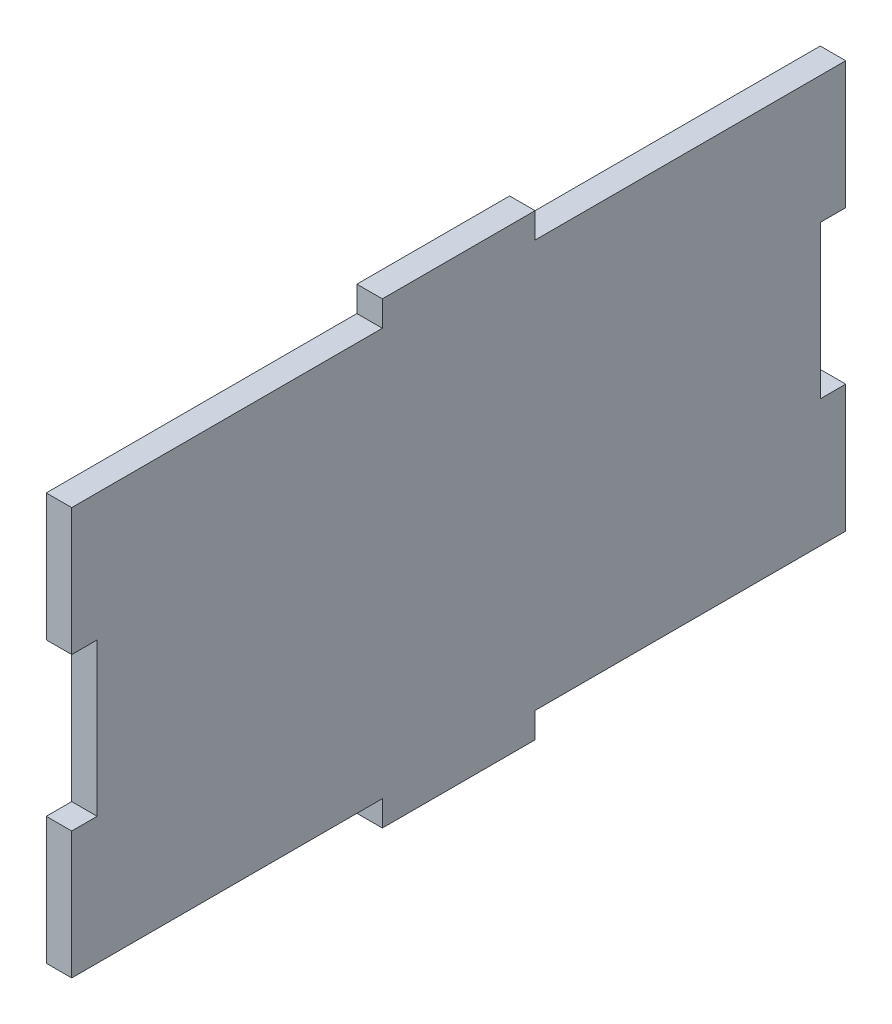
SolidWorks part; units mm, degrees
ref_plane "Front Plane" through (0, 0, 0) normal (0, 0, 1) x (1, 0, 0)
ref_plane "Top Plane" through (0, 0, 0) normal (0, 1, 0) x (1, 0, 0)
ref_plane "Right Plane" through (0, 0, 0) normal (1, 0, 0) x (0, 0, -1)
sketch "Sketch1" plane through (0, 0, 0) normal (1, 0, 0) x (0, 0, -1)
  line L0 (48.26, 50.8) -> (48.26, -7.345) construction
  line L1 (0, 0) -> (38.735, 0)
  line L2 (0, 0) -> (0, 15.875)
  line L3 (0, 50.8) -> (38.735, 50.8)
  line L4 (96.52, 0) -> (96.52, 15.875)
  line L5 (38.735, 50.8) -> (38.735, 53.975)
  line L6 (38.735, 53.975) -> (57.785, 53.975)
  line L7 (57.785, 53.975) -> (57.785, 50.8)
  line L8 (48.26, 53.975) -> (48.26, 50.8) construction
  line L9 (96.52, 25.4) -> (-8.8493, 25.4) construction
  line L10 (0, 34.925) -> (3.175, 34.925)
  line L11 (3.175, 34.925) -> (3.175, 15.875)
  line L12 (3.175, 15.875) -> (0, 15.875)
  line L13 (0, 34.925) -> (0, 50.8)
  line L14 (57.785, 50.8) -> (96.52, 50.8)
  line L15 (93.345, 15.875) -> (96.52, 15.875)
  line L16 (93.345, 34.925) -> (93.345, 15.875)
  line L17 (96.52, 34.925) -> (93.345, 34.925)
  line L18 (57.785, -3.175) -> (57.785, 0)
  line L19 (38.735, 0) -> (38.735, -3.175)
  line L20 (38.735, -3.175) -> (57.785, -3.175)
  line L21 (96.52, 34.925) -> (96.52, 50.8)
  line L22 (57.785, 0) -> (96.52, 0)
  point P17 (3.175, 25.4)
  dimension "D1" = 50.8
  dimension "D2" = 96.52
  dimension "D3" = 19.05
  dimension "D4" = 3.175
  dimension "D5" = 3.175
  dimension "D6" = 19.05
extrude "Boss-Extrude1" add sketch "Sketch1" along normal blind 3.175
